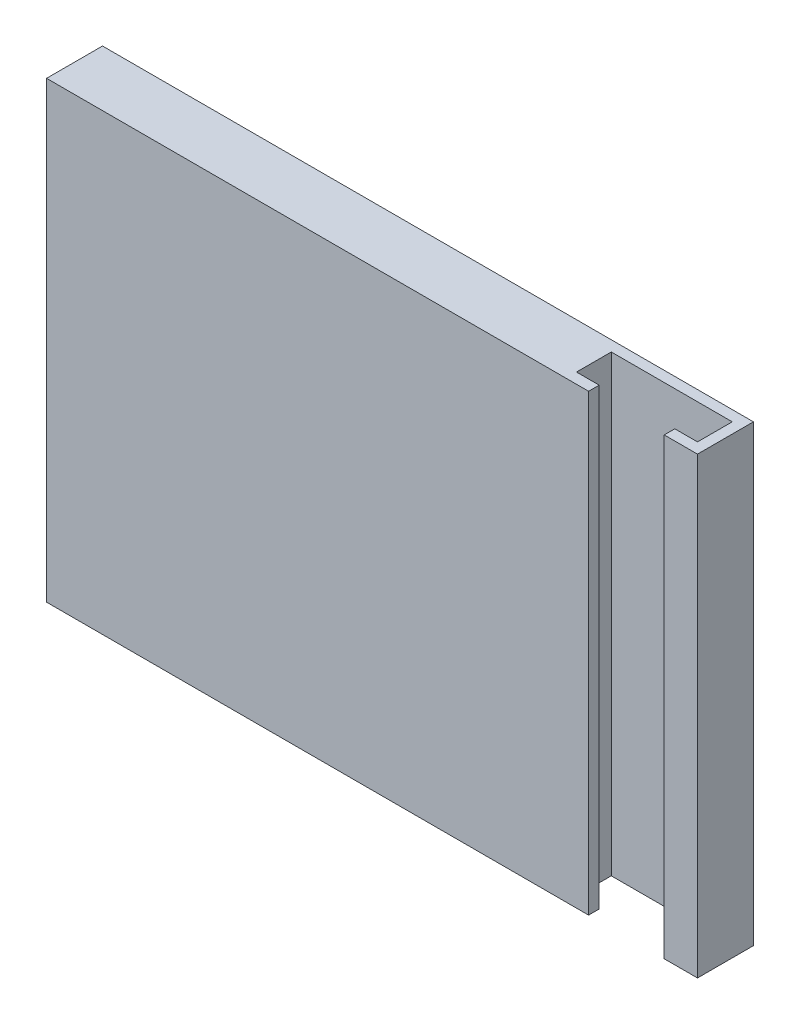
SolidWorks part; units mm, degrees
ref_plane "Front Plane" through (0, 0, 0) normal (0, 0, 1) x (1, 0, 0)
ref_plane "Top Plane" through (0, 0, 0) normal (0, 1, 0) x (1, 0, 0)
ref_plane "Right Plane" through (0, 0, 0) normal (1, 0, 0) x (0, 0, -1)
sketch "Sketch1" plane through (0, 0, 0) normal (0, 1, 0) x (1, 0, 0)
  line L0 (131.5033, 178.2125) -> (146.5033, 178.2125)
  line L1 (146.5033, 178.2125) -> (146.5033, 201.2125)
  line L2 (146.5033, 201.2125) -> (66.5033, 201.2125)
  line L3 (66.5033, 201.2125) -> (66.5033, 178.2125)
  line L4 (66.5033, 178.2125) -> (81.5033, 178.2125)
  line L5 (131.5033, 171.2125) -> (153.5033, 171.2125)
  line L6 (153.5033, 171.2125) -> (153.5033, 208.2125)
  line L7 (153.5033, 208.2125) -> (59.5033, 208.2125)
  line L8 (59.5033, 208.2125) -> (59.5033, 171.2125)
  line L9 (59.5033, 171.2125) -> (81.5033, 171.2125)
  line L10 (131.5033, 178.2125) -> (131.5033, 171.2125)
  line L11 (81.5033, 178.2125) -> (81.5033, 171.2125)
  line L16 (126.5033, 138.7125) -> (126.5033, 200.7125) construction
  line L17 (86.5033, 200.7125) -> (86.5033, 178.7125) construction
  line L18 (131.5033, 178.7125) -> (138.5033, 178.7125) construction
  dimension "D1" = 5
  dimension "D2" = 23
  dimension "D3" = 0.5
  dimension "D4" = 15
  dimension "D5" = 5
  dimension "D6" = 7
extrude "Boss-Extrude1" add sketch "Sketch1" along normal mid plane 300
sketch "Sketch2" plane through (0, 0, -171.2125) normal (0, 0, 1) x (1, 0, 0)
  line L0 (59.5033, 150) -> (59.5033, -150)
  line L1 (59.5033, 150) -> (-276.9194, 150)
  line L2 (59.5033, -150) -> (-276.9194, -150)
  line L3 (-276.9194, 150) -> (-276.9194, -150)
extrude "Boss-Extrude2" add sketch "Sketch2" against normal up to surface (37 mm away) up to face at (106.5033, 0, -208.2125)
sketch "Sketch3" plane through (0, 0, 0) normal (0, 1, 0) x (1, 0, 0)
  line L0 (-206.1537, 171.2125) -> (-134.8471, 171.2125)
  line L1 (-206.1537, 171.2125) -> (-206.1537, -80.5989)
  line L2 (-134.8471, 171.2125) -> (-134.8471, -80.5989)
  line L3 (-206.1537, -80.5989) -> (-134.8471, -80.5989)
  line L4 (-276.9194, 171.2125) -> (81.5033, 171.2125) construction
  line L5 (-23.6492, -56.6604) -> (-126.3876, -159.3988)
  line L6 (-23.6492, -56.6604) -> (-196.1697, 115.8601)
  line L7 (-126.3876, -159.3988) -> (-298.9081, 13.1217)
  line L8 (-196.1697, 115.8601) -> (-298.9081, 13.1217)
  line L9 (-74.2462, -107.2574) -> (0, -33.0112) construction
  line L10 (-242.8816, 69.1482) -> (-70.3611, -103.3723)
  line L11 (-170.5004, -80.5989) -> (-170.5004, 90.1908)
  line L12 (-170.5004, -3.233) -> (-304.4025, -109.7527)
  point P19 (-170.5004, -4.0984)
